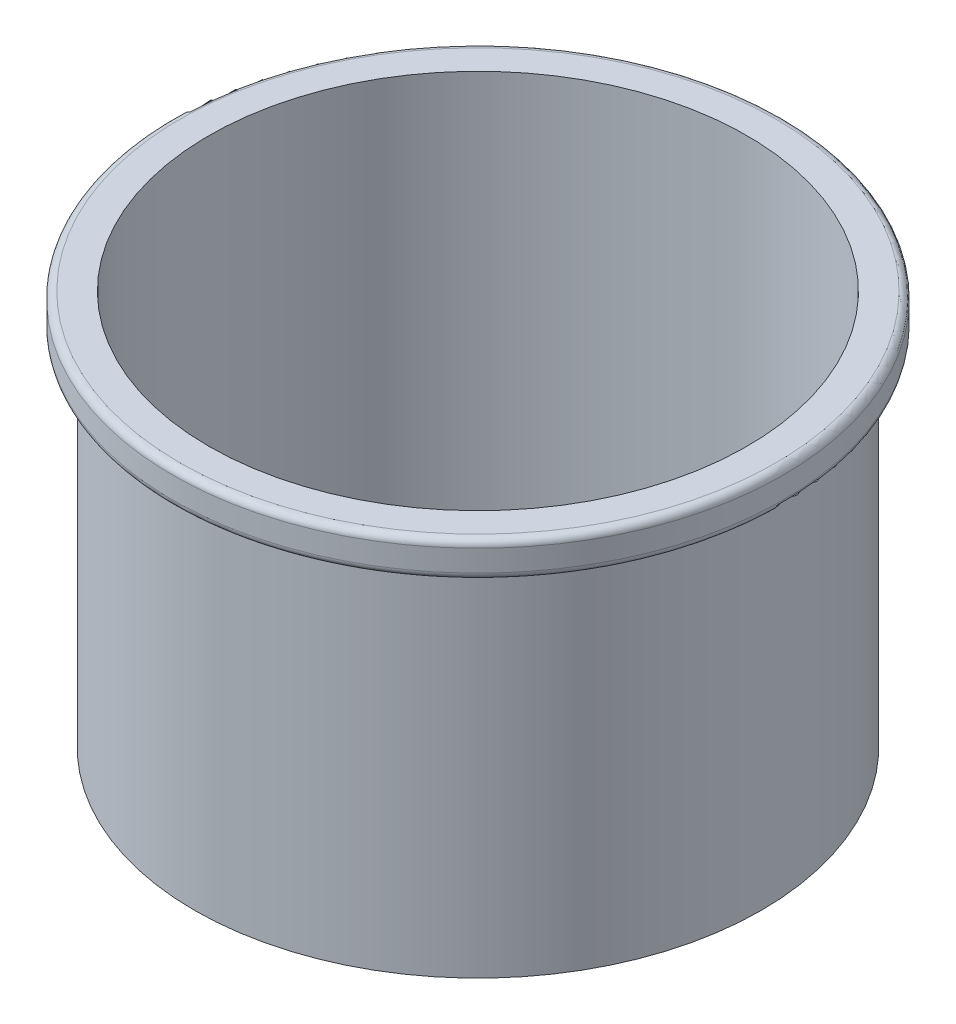
SolidWorks part; units mm, degrees
ref_plane "Front Plane" through (0, 0, 0) normal (0, 0, 1) x (1, 0, 0)
ref_plane "Top Plane" through (0, 0, 0) normal (0, 1, 0) x (1, 0, 0)
ref_plane "Right Plane" through (0, 0, 0) normal (1, 0, 0) x (0, 0, -1)
sketch "Sketch1" plane through (0, 0, 0) normal (0, 1, 0) x (1, 0, 0)
  circle A0 centre (0, 0) radius 79
  dimension "D1" = 158
extrude "Boss-Extrude1" add sketch "Sketch1" along normal blind 110
shell "Shell1" thickness 4
ref_axis "Axis1" through (0, -5.5, 0) along (0, 1, 0)
sketch "Sketch2" plane through (0, 0, 0) normal (1, 0, 0) x (0, 0, -1)
  line L0 (79, 110) -> (83, 110)
  line L1 (85, 108) -> (85, 102)
  line L2 (83, 100) -> (79, 100)
  line L3 (79, 0) -> (79, 110) construction
  line L4 (79, 110) -> (79, 100)
  arc A0 (85, 102) -> (83, 100) centre (83, 102) cw
  arc A1 (85, 108) -> (83, 110) centre (83, 108) ccw
  point P9 (85, 100)
  point P12 (85, 110)
  dimension "D3" = 2
  dimension "D1" = 6
  dimension "D2" = 10
revolve "Revolve1" add sketch "Sketch2" angle 360 about axis through (0, -5.5, 0) along (0, 1, 0)
